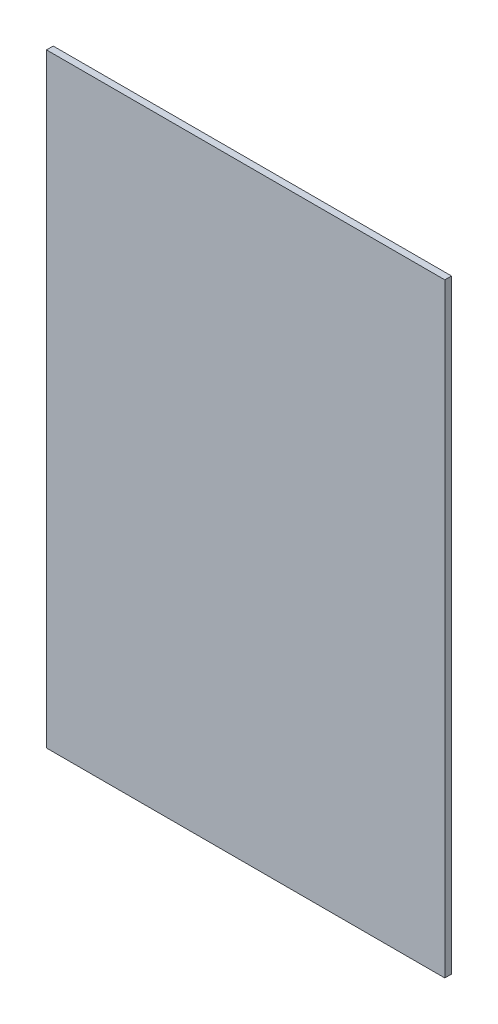
SolidWorks part; units mm, degrees
ref_plane "Front" through (0, 0, 0) normal (0, 0, 1) x (1, 0, 0)
ref_plane "Top" through (0, 0, 0) normal (0, 1, 0) x (1, 0, 0)
ref_plane "Right" through (0, 0, 0) normal (1, 0, 0) x (0, 0, -1)
other "Configuration Table"
sketch "Sketch1" plane through (0, 0, 0) normal (0, 0, 1) x (1, 0, 0)
  line L1 (0, 0) -> (415, 0)
  line L2 (0, 0) -> (0, 630)
  line L3 (0, 630) -> (415, 630)
  line L4 (415, 0) -> (415, 630)
  dimension "D1" = 415
  dimension "D2" = 630
extrude "Base-Extrude" add sketch "Sketch1" along normal blind 7
sketch "Sketch19" plane through (0, 0, 0) normal (0, 0, -1) x (-1, 0, 0)
  line L4 (-58.1, 58.1) -> (-58.1, 571.9)
  line L5 (-58.1, 58.1) -> (-58.1, 571.9)
  line L6 (-58.1, 571.9) -> (-356.9, 571.9)
  line L7 (-58.1, 571.9) -> (-356.9, 571.9)
  line L8 (-356.9, 571.9) -> (-356.9, 58.1)
  line L9 (-356.9, 571.9) -> (-356.9, 58.1)
  line L10 (-356.9, 58.1) -> (-58.1, 58.1)
  line L11 (-356.9, 58.1) -> (-58.1, 58.1)
  line L12 (-125.3, 125.3) -> (-125.3, 504.7)
  line L13 (-125.3, 125.3) -> (-125.3, 504.7)
  line L14 (-125.3, 504.7) -> (-289.7, 504.7)
  line L15 (-125.3, 504.7) -> (-289.7, 504.7)
  line L16 (-289.7, 504.7) -> (-289.7, 125.3)
  line L17 (-289.7, 504.7) -> (-289.7, 125.3)
  line L18 (-289.7, 125.3) -> (-125.3, 125.3)
  line L19 (-289.7, 125.3) -> (-125.3, 125.3)
  dimension "D1" = 58.1
  dimension "D2" = 125.3
extrude "Cut-Extrude1" cut sketch "Sketch19" against normal blind 5
chamfer "Chamfer1" distance 4 angle 45 8 edges at (207.5, 58.1, 5) (356.9, 315, 5) (207.5, 571.9, 5) (58.1, 315, 5) (289.7, 315, 5) (207.5, 125.3, 5) (125.3, 315, 5) (207.5, 504.7, 5)
